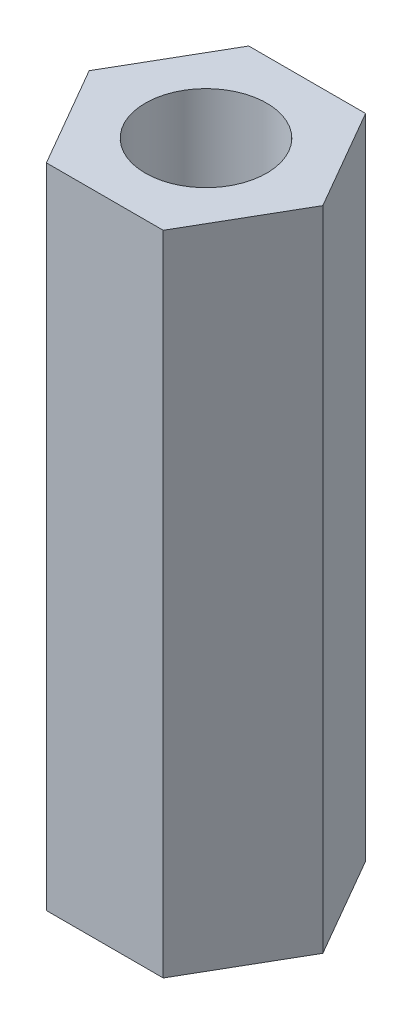
SolidWorks part; units mm, degrees
material "ABS"
ref_plane "Alzado" through (0, 0, 0) normal (0, 0, 1) x (1, 0, 0)
ref_plane "Planta" through (0, 0, 0) normal (0, 1, 0) x (1, 0, 0)
ref_plane "Vista lateral" through (0, 0, 0) normal (1, 0, 0) x (0, 0, -1)
sketch "Croquis1" plane through (0, 0, 0) normal (0, 1, 0) x (1, 0, 0)
  line L1 (1.4434, -2.5) -> (2.8868, 0)
  line L2 (2.8868, 0) -> (1.4434, 2.5)
  line L3 (1.4434, 2.5) -> (-1.4434, 2.5)
  line L4 (-1.4434, 2.5) -> (-2.8868, 0)
  line L5 (-2.8868, 0) -> (-1.4434, -2.5)
  line L6 (-1.4434, -2.5) -> (1.4434, -2.5)
  circle A0 centre (0, 0) radius 2.5 construction
  circle A1 centre (0, 0) radius 1.5
  dimension "D2" = 3
  dimension "D1" = 5
extrude "Saliente-Extruir1" add sketch "Croquis1" along normal mid plane 12
sketch "草图1" plane through (0, 6, 0) normal (0, 1, 0) x (1, 0, 0)
  line L6 (-1.4434, -2.5) -> (1.4434, -2.5)
  line L7 (1.4434, -2.5) -> (2.8868, 0)
  line L8 (2.8868, 0) -> (1.4434, 2.5)
  line L9 (1.4434, 2.5) -> (-1.4434, 2.5)
  line L10 (-1.4434, 2.5) -> (-2.8868, 0)
  line L11 (-2.8868, 0) -> (-1.4434, -2.5)
  line L12 (-1.4434, -2.5) -> (1.4434, -2.5)
  line L13 (1.4434, -2.5) -> (2.8868, 0)
  line L14 (2.8868, 0) -> (1.4434, 2.5)
  line L15 (1.4434, 2.5) -> (-1.4434, 2.5)
  line L16 (-1.4434, 2.5) -> (-2.8868, 0)
  line L17 (-2.8868, 0) -> (-1.4434, -2.5)
  circle A0 centre (0, 0) radius 1.5 construction
  circle A1 centre (0, 0) radius 1.5
  dimension "D1" = 0
extrude "凸台-拉伸1" add sketch "草图1" along normal blind 4
